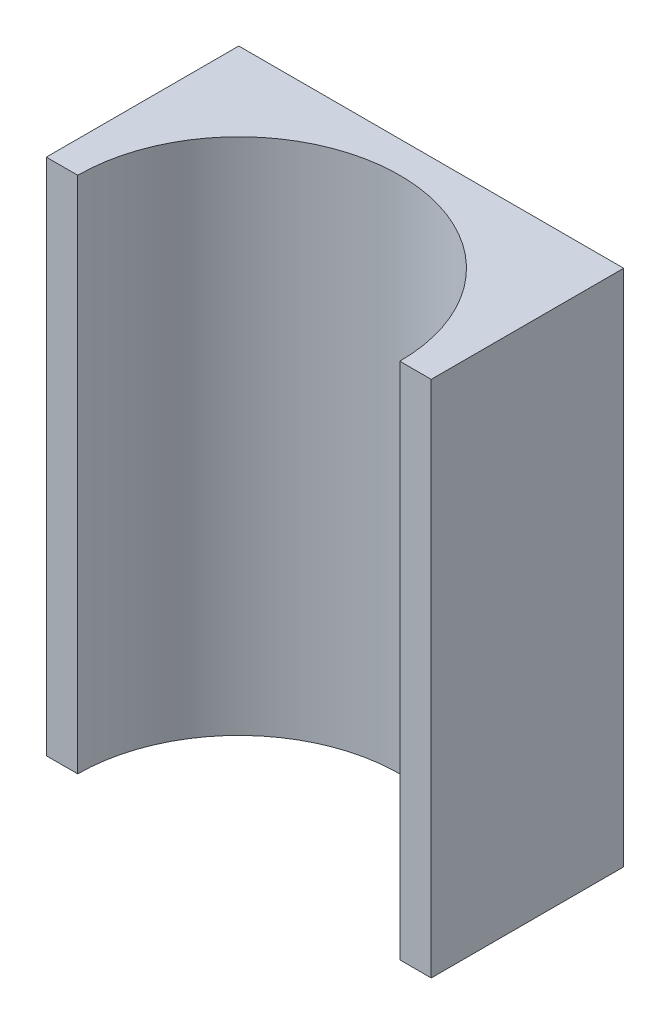
SolidWorks part; units mm, degrees
ref_plane "Front Plane" through (0, 0, 0) normal (0, 0, 1) x (1, 0, 0)
ref_plane "Top Plane" through (0, 0, 0) normal (0, 1, 0) x (1, 0, 0)
ref_plane "Right Plane" through (0, 0, 0) normal (1, 0, 0) x (0, 0, -1)
sketch "Sketch1" plane through (0, 0, 0) normal (0, 1, 0) x (1, 0, 0)
  line L0 (-1244.6, 0) -> (-1041.4, 0)
  line L1 (1041.4, 0) -> (1244.6, 0)
  line L2 (-1244.6, 0) -> (-1244.6, 1244.6)
  line L3 (-1244.6, 1244.6) -> (0, 1244.6)
  line L4 (1244.6, 0) -> (1244.6, 1244.6)
  line L5 (0, 1244.6) -> (1244.6, 1244.6)
  arc A0 (-1041.4, 0) -> (1041.4, 0) centre (0, 0) cw
  dimension "D1" = 90
extrude "Boss-Extrude1" add sketch "Sketch1" along normal blind 3352.8 contours L1 L4 L5 L3 L2 L0 A0
